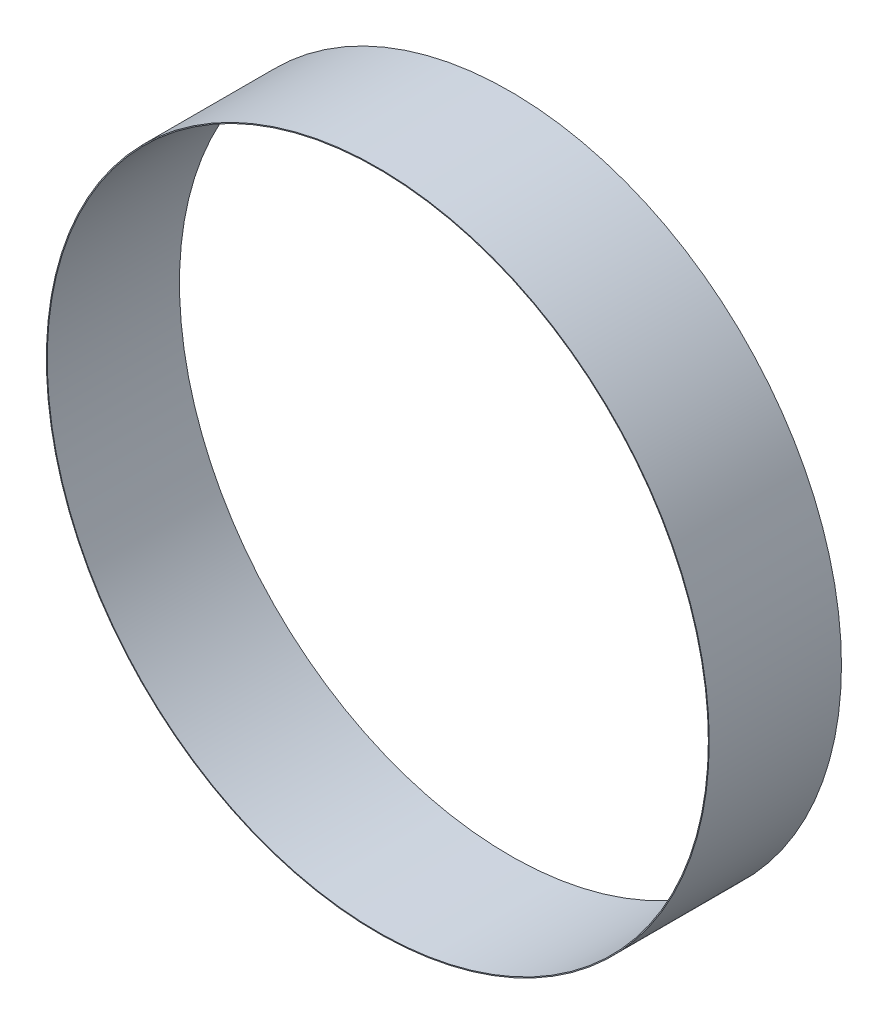
SolidWorks part; units mm, degrees
ref_plane "Ebene vorne" through (0, 0, 0) normal (0, 0, 1) x (1, 0, 0)
ref_plane "Ebene oben" through (0, 0, 0) normal (0, 1, 0) x (1, 0, 0)
ref_plane "Ebene rechts" through (0, 0, 0) normal (1, 0, 0) x (0, 0, -1)
sketch "Sketch1" plane through (0, 0, 0) normal (0, 0, 1) x (1, 0, 0)
  circle A0 centre (0, 0) radius 75.2
  circle A1 centre (0, 0) radius 75
  dimension "D1" = 150
  dimension "D2" = 0.2
extrude "Boss-Extrude1" add sketch "Sketch1" along normal blind 30
